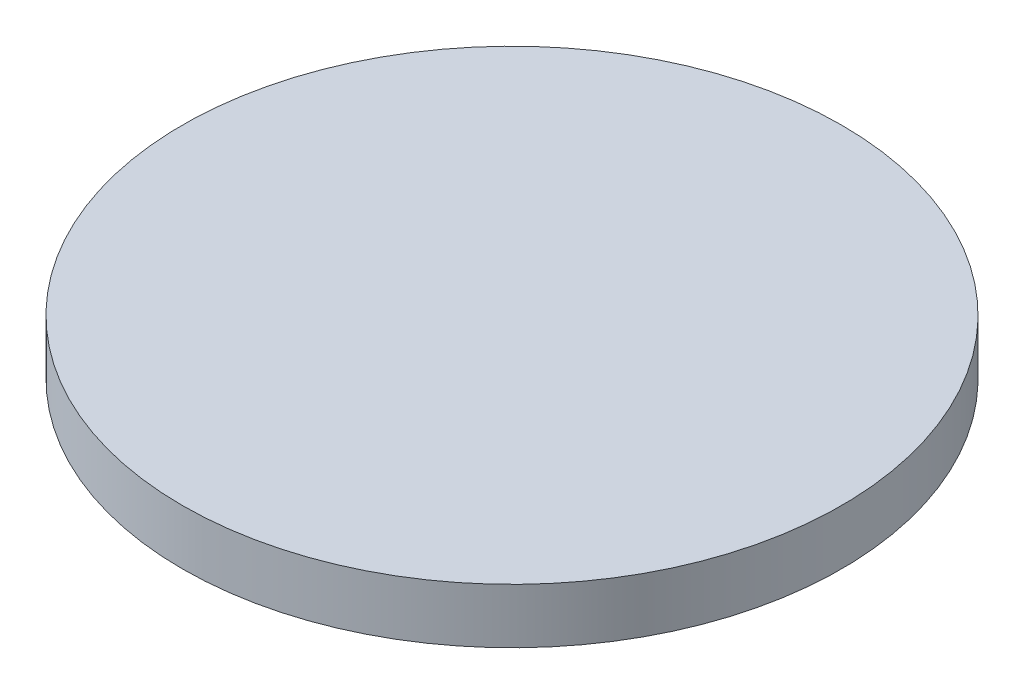
SolidWorks part; units mm, degrees
material "AISI 304"
ref_plane "Front Plane" through (0, 0, 0) normal (0, 0, 1) x (1, 0, 0)
ref_plane "Top Plane" through (0, 0, 0) normal (0, 1, 0) x (1, 0, 0)
ref_plane "Right Plane" through (0, 0, 0) normal (1, 0, 0) x (0, 0, -1)
sketch "Main Shape Profile" plane through (0, 0, 0) normal (0, 0, 1) x (1, 0, 0)
  line L0 (0, 0) -> (0, -36934.052) construction
  line L1 (0, 0) -> (38.1, 0)
  line L2 (38.1, 0) -> (38.1, 6.35)
  line L3 (38.1, 6.35) -> (0, 6.35)
  line L4 (0, 6.35) -> (0, 0)
  dimension "LOX OD" = 76.2
  dimension "LOX Thickness" = 6.35
revolve "Main Shape" add sketch "Main Shape Profile" angle 360 about L0
